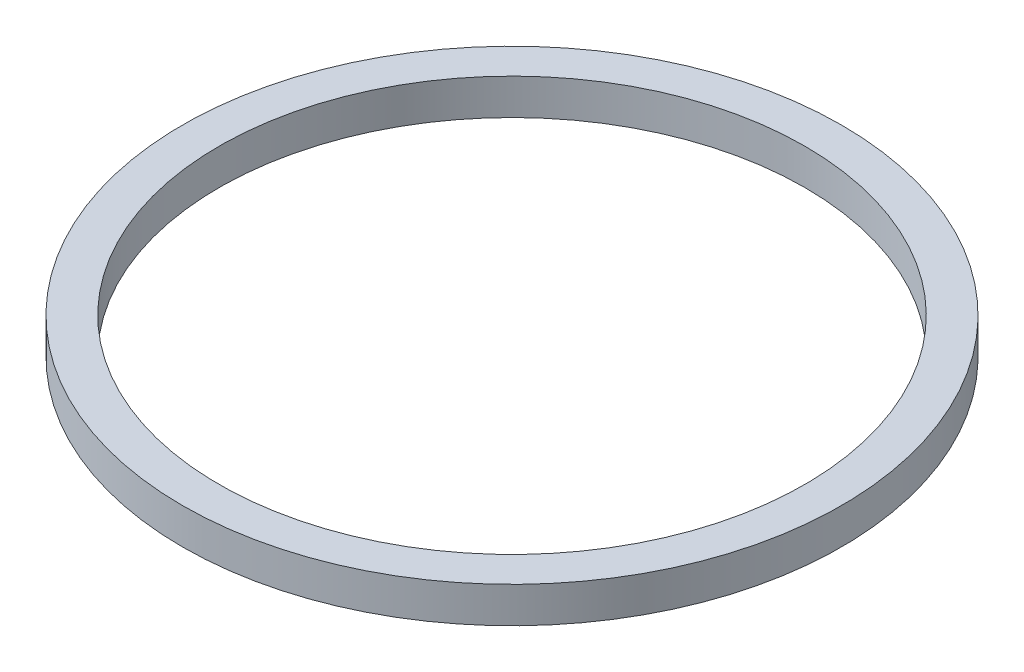
SolidWorks part; units mm, degrees
material "Hexcel AS4C (3000 Filaments)"
ref_plane "Front Plane" through (0, 0, 0) normal (0, 0, 1) x (1, 0, 0)
ref_plane "Top Plane" through (0, 0, 0) normal (0, 1, 0) x (1, 0, 0)
ref_plane "Right Plane" through (0, 0, 0) normal (1, 0, 0) x (0, 0, -1)
sketch "Sketch1" plane through (0, 0, 0) normal (0, 0, 1) x (1, 0, 0)
  line L0 (-60, 8.1325) -> (-60, 0.785) construction
  line L1 (-67.5, 8.1325) -> (-67.5, 0.785) construction
  line L2 (-60, 8.1325) -> (-60, 0.785)
  line L3 (-67.5, 8.1325) -> (-67.5, 0.785)
  line L4 (-60, 8.1325) -> (-67.5, 8.1325)
  line L5 (-60, 0.785) -> (-67.5, 0.785)
  line L6 (0, -200069.0475) -> (0, 200086.9028) construction
  line L7 (0, -200069.0475) -> (0, 200086.9028) construction
revolve "Revolve1" add sketch "Sketch1" angle 360 about L7
